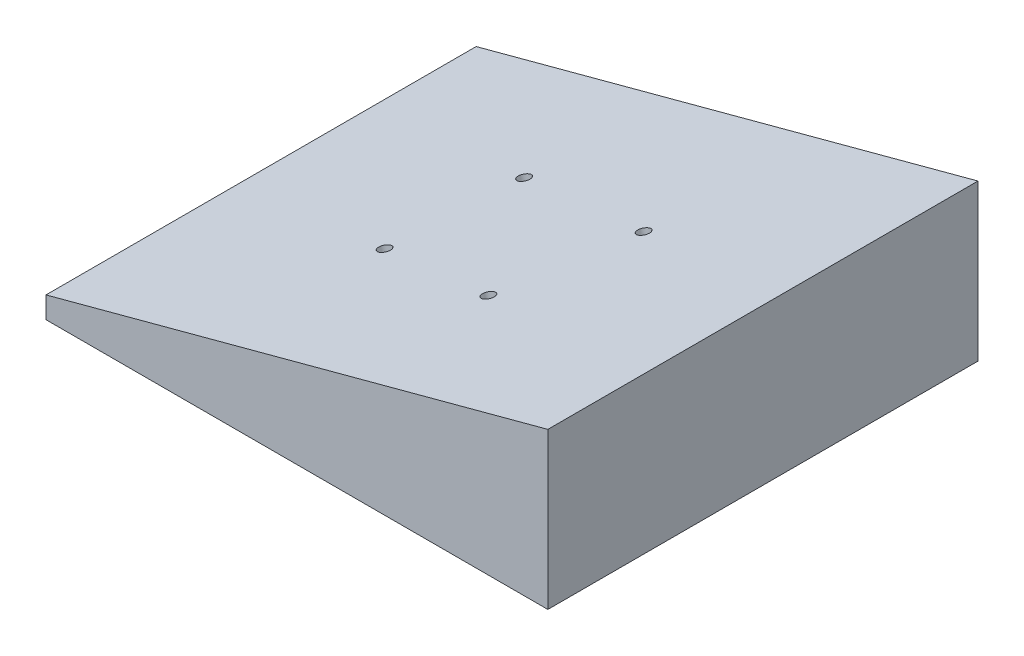
SolidWorks part; units mm, degrees
ref_plane "前视基准面" through (0, 0, 0) normal (0, 0, 1) x (1, 0, 0)
ref_plane "上视基准面" through (0, 0, 0) normal (0, 1, 0) x (1, 0, 0)
ref_plane "右视基准面" through (0, 0, 0) normal (1, 0, 0) x (0, 0, -1)
other "Configuration Table"
sketch "草图1" plane through (0, 0, 0) normal (0, 0, 1) x (1, 0, 0)
  line L0 (0, 0) -> (70, 0)
  line L1 (70, 0) -> (70, 21.7564)
  line L2 (70, 21.7564) -> (0, 3)
  line L3 (0, 3) -> (0, 0)
extrude "凸台-拉伸1" add sketch "草图1" along normal blind 60
sketch "草图2" plane through (-0.75, 2.799, 0) normal (-0.2588, 0.9659, 0) x (0.9659, 0.2588, 0)
  circle A0 centre (27.8901, -19.503) radius 0.85
  circle A1 centre (48.8981, -23.123) radius 0.85
  circle A2 centre (44.4711, -40.502) radius 0.85
  circle A3 centre (26.2701, -37.391) radius 0.85
extrude "切除-拉伸1" cut sketch "草图2" against normal mid plane 60
